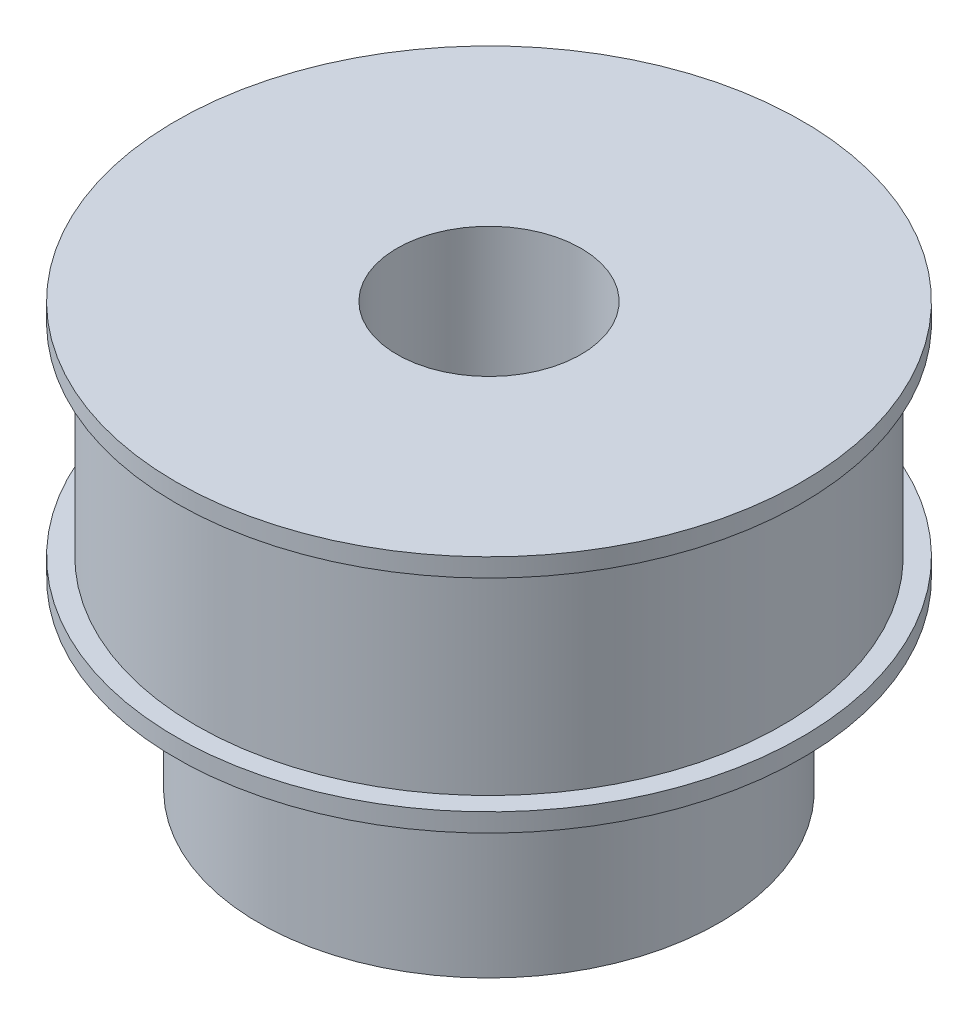
SolidWorks part; units mm, degrees
ref_plane "前视基准面" through (0, 0, 0) normal (0, 0, 1) x (1, 0, 0)
ref_plane "上视基准面" through (0, 0, 0) normal (0, 1, 0) x (1, 0, 0)
ref_plane "右视基准面" through (0, 0, 0) normal (1, 0, 0) x (0, 0, -1)
other "Configuration Table"
sketch "草图1" plane through (0, 0, 0) normal (0, 1, 0) x (1, 0, 0)
  circle A0 centre (0, 0) radius 15.915
  dimension "D1" = 31.83
extrude "凸台-拉伸1" add sketch "草图1" along normal blind 11
sketch "草图2" plane through (0, 11, 0) normal (0, 1, 0) x (1, 0, 0)
  circle A0 centre (0, 0) radius 17
  dimension "D1" = 34
extrude "凸台-拉伸2" add sketch "草图2" along normal blind 1
sketch "草图3" plane through (0, 0, 0) normal (0, -1, 0) x (1, 0, 0)
  circle A1 centre (0, 0) radius 17
  circle A2 centre (0, 0) radius 17
  dimension "D1" = 0
extrude "凸台-拉伸3" add sketch "草图3" along normal blind 1
sketch "草图4" plane through (0, -1, 0) normal (0, -1, 0) x (1, 0, 0)
  circle A0 centre (0, 0) radius 5
  dimension "D1" = 10
extrude "切除-拉伸1" cut sketch "草图4" against normal through all
sketch "草图5" plane through (0, -1, 0) normal (0, -1, 0) x (1, 0, 0)
  circle A0 centre (0, 0) radius 5
  circle A1 centre (0, 0) radius 12.5
  dimension "D1" = 25
extrude "凸台-拉伸4" add sketch "草图5" along normal blind 10
